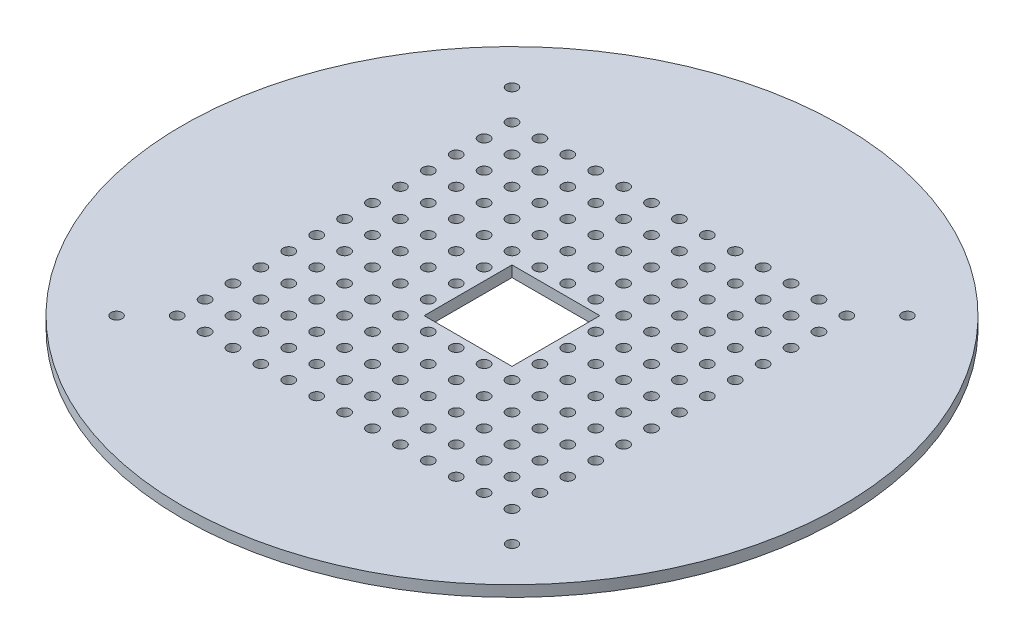
SolidWorks part; units mm, degrees
ref_plane "前视基准面" through (0, 0, 0) normal (0, 0, 1) x (1, 0, 0)
ref_plane "上视基准面" through (0, 0, 0) normal (0, 1, 0) x (1, 0, 0)
ref_plane "右视基准面" through (0, 0, 0) normal (1, 0, 0) x (0, 0, -1)
sketch "草图1" plane through (0, 0, 0) normal (0, 1, 0) x (1, 0, 0)
  line L0 (76.2, 76.2) -> (63.5, 76.2) construction
  circle A0 centre (0, 0) radius 150
  circle A1 centre (90, -90) radius 2.5
  circle A2 centre (90, 90) radius 2.5
  circle A3 centre (-90, -90) radius 2.5
  circle A4 centre (-90, 90) radius 2.5
  circle A5 centre (76.2, 76.2) radius 2.54
  circle A6 centre (63.5, 76.2) radius 2.54
  circle A7 centre (50.8, 76.2) radius 2.54
  circle A8 centre (38.1, 76.2) radius 2.54
  circle A9 centre (25.4, 76.2) radius 2.54
  circle A10 centre (12.7, 76.2) radius 2.54
  circle A11 centre (0, 76.2) radius 2.54
  circle A12 centre (-12.7, 76.2) radius 2.54
  circle A13 centre (-25.4, 76.2) radius 2.54
  circle A14 centre (-38.1, 76.2) radius 2.54
  circle A15 centre (-50.8, 76.2) radius 2.54
  circle A16 centre (-63.5, 76.2) radius 2.54
  circle A17 centre (-76.2, 76.2) radius 2.54
  circle A18 centre (63.5, 63.5) radius 2.54
  circle A19 centre (50.8, 63.5) radius 2.54
  circle A20 centre (38.1, 63.5) radius 2.54
  circle A21 centre (25.4, 63.5) radius 2.54
  circle A22 centre (12.7, 63.5) radius 2.54
  circle A23 centre (0, 63.5) radius 2.54
  circle A24 centre (-12.7, 63.5) radius 2.54
  circle A25 centre (-25.4, 63.5) radius 2.54
  circle A26 centre (-38.1, 63.5) radius 2.54
  circle A27 centre (-50.8, 63.5) radius 2.54
  circle A28 centre (-63.5, 63.5) radius 2.54
  circle A29 centre (-76.2, 63.5) radius 2.54
  circle A30 centre (63.5, 50.8) radius 2.54
  circle A31 centre (50.8, 50.8) radius 2.54
  circle A32 centre (38.1, 50.8) radius 2.54
  circle A33 centre (25.4, 50.8) radius 2.54
  circle A34 centre (12.7, 50.8) radius 2.54
  circle A35 centre (0, 50.8) radius 2.54
  circle A36 centre (-12.7, 50.8) radius 2.54
  circle A37 centre (-25.4, 50.8) radius 2.54
  circle A38 centre (-38.1, 50.8) radius 2.54
  circle A39 centre (-50.8, 50.8) radius 2.54
  circle A40 centre (-63.5, 50.8) radius 2.54
  circle A41 centre (-76.2, 50.8) radius 2.54
  circle A42 centre (63.5, 38.1) radius 2.54
  circle A43 centre (50.8, 38.1) radius 2.54
  circle A44 centre (38.1, 38.1) radius 2.54
  circle A45 centre (25.4, 38.1) radius 2.54
  circle A46 centre (12.7, 38.1) radius 2.54
  circle A47 centre (0, 38.1) radius 2.54
  circle A48 centre (-12.7, 38.1) radius 2.54
  circle A49 centre (-25.4, 38.1) radius 2.54
  circle A50 centre (-38.1, 38.1) radius 2.54
  circle A51 centre (-50.8, 38.1) radius 2.54
  circle A52 centre (-63.5, 38.1) radius 2.54
  circle A53 centre (-76.2, 38.1) radius 2.54
  circle A54 centre (63.5, 25.4) radius 2.54
  circle A55 centre (50.8, 25.4) radius 2.54
  circle A56 centre (38.1, 25.4) radius 2.54
  circle A57 centre (25.4, 25.4) radius 2.54
  circle A58 centre (12.7, 25.4) radius 2.54
  circle A59 centre (0, 25.4) radius 2.54
  circle A60 centre (-12.7, 25.4) radius 2.54
  circle A61 centre (-25.4, 25.4) radius 2.54
  circle A62 centre (-38.1, 25.4) radius 2.54
  circle A63 centre (-50.8, 25.4) radius 2.54
  circle A64 centre (-63.5, 25.4) radius 2.54
  circle A65 centre (-76.2, 25.4) radius 2.54
  circle A66 centre (63.5, 12.7) radius 2.54
  circle A67 centre (50.8, 12.7) radius 2.54
  circle A68 centre (38.1, 12.7) radius 2.54
  circle A69 centre (25.4, 12.7) radius 2.54
  circle A70 centre (12.7, 12.7) radius 2.54
  circle A71 centre (0, 12.7) radius 2.54
  circle A72 centre (-12.7, 12.7) radius 2.54
  circle A73 centre (-25.4, 12.7) radius 2.54
  circle A74 centre (-38.1, 12.7) radius 2.54
  circle A75 centre (-50.8, 12.7) radius 2.54
  circle A76 centre (-63.5, 12.7) radius 2.54
  circle A77 centre (-76.2, 12.7) radius 2.54
  circle A78 centre (63.5, 0) radius 2.54
  circle A79 centre (50.8, 0) radius 2.54
  circle A80 centre (38.1, 0) radius 2.54
  circle A81 centre (25.4, 0) radius 2.54
  circle A82 centre (12.7, 0) radius 2.54
  circle A83 centre (0, 0) radius 2.54
  circle A84 centre (-12.7, 0) radius 2.54
  circle A85 centre (-25.4, 0) radius 2.54
  circle A86 centre (-38.1, 0) radius 2.54
  circle A87 centre (-50.8, 0) radius 2.54
  circle A88 centre (-63.5, 0) radius 2.54
  circle A89 centre (-76.2, 0) radius 2.54
  circle A90 centre (63.5, -12.7) radius 2.54
  circle A91 centre (50.8, -12.7) radius 2.54
  circle A92 centre (38.1, -12.7) radius 2.54
  circle A93 centre (25.4, -12.7) radius 2.54
  circle A94 centre (12.7, -12.7) radius 2.54
  circle A95 centre (0, -12.7) radius 2.54
  circle A96 centre (-12.7, -12.7) radius 2.54
  circle A97 centre (-25.4, -12.7) radius 2.54
  circle A98 centre (-38.1, -12.7) radius 2.54
  circle A99 centre (-50.8, -12.7) radius 2.54
  circle A100 centre (-63.5, -12.7) radius 2.54
  circle A101 centre (-76.2, -12.7) radius 2.54
  circle A102 centre (63.5, -25.4) radius 2.54
  circle A103 centre (50.8, -25.4) radius 2.54
  circle A104 centre (38.1, -25.4) radius 2.54
  circle A105 centre (25.4, -25.4) radius 2.54
  circle A106 centre (12.7, -25.4) radius 2.54
  circle A107 centre (0, -25.4) radius 2.54
  circle A108 centre (-12.7, -25.4) radius 2.54
  circle A109 centre (-25.4, -25.4) radius 2.54
  circle A110 centre (-38.1, -25.4) radius 2.54
  circle A111 centre (-50.8, -25.4) radius 2.54
  circle A112 centre (-63.5, -25.4) radius 2.54
  circle A113 centre (-76.2, -25.4) radius 2.54
  circle A114 centre (63.5, -38.1) radius 2.54
  circle A115 centre (50.8, -38.1) radius 2.54
  circle A116 centre (38.1, -38.1) radius 2.54
  circle A117 centre (25.4, -38.1) radius 2.54
  circle A118 centre (12.7, -38.1) radius 2.54
  circle A119 centre (0, -38.1) radius 2.54
  circle A120 centre (-12.7, -38.1) radius 2.54
  circle A121 centre (-25.4, -38.1) radius 2.54
  circle A122 centre (-38.1, -38.1) radius 2.54
  circle A123 centre (-50.8, -38.1) radius 2.54
  circle A124 centre (-63.5, -38.1) radius 2.54
  circle A125 centre (-76.2, -38.1) radius 2.54
  circle A126 centre (63.5, -50.8) radius 2.54
  circle A127 centre (50.8, -50.8) radius 2.54
  circle A128 centre (38.1, -50.8) radius 2.54
  circle A129 centre (25.4, -50.8) radius 2.54
  circle A130 centre (12.7, -50.8) radius 2.54
  circle A131 centre (0, -50.8) radius 2.54
  circle A132 centre (-12.7, -50.8) radius 2.54
  circle A133 centre (-25.4, -50.8) radius 2.54
  circle A134 centre (-38.1, -50.8) radius 2.54
  circle A135 centre (-50.8, -50.8) radius 2.54
  circle A136 centre (-63.5, -50.8) radius 2.54
  circle A137 centre (-76.2, -50.8) radius 2.54
  circle A138 centre (63.5, -63.5) radius 2.54
  circle A139 centre (50.8, -63.5) radius 2.54
  circle A140 centre (38.1, -63.5) radius 2.54
  circle A141 centre (25.4, -63.5) radius 2.54
  circle A142 centre (12.7, -63.5) radius 2.54
  circle A143 centre (0, -63.5) radius 2.54
  circle A144 centre (-12.7, -63.5) radius 2.54
  circle A145 centre (-25.4, -63.5) radius 2.54
  circle A146 centre (-38.1, -63.5) radius 2.54
  circle A147 centre (-50.8, -63.5) radius 2.54
  circle A148 centre (-63.5, -63.5) radius 2.54
  circle A149 centre (-76.2, -63.5) radius 2.54
  circle A150 centre (63.5, -76.2) radius 2.54
  circle A151 centre (50.8, -76.2) radius 2.54
  circle A152 centre (38.1, -76.2) radius 2.54
  circle A153 centre (25.4, -76.2) radius 2.54
  circle A154 centre (12.7, -76.2) radius 2.54
  circle A155 centre (0, -76.2) radius 2.54
  circle A156 centre (-12.7, -76.2) radius 2.54
  circle A157 centre (-25.4, -76.2) radius 2.54
  circle A158 centre (-38.1, -76.2) radius 2.54
  circle A159 centre (-50.8, -76.2) radius 2.54
  circle A160 centre (-63.5, -76.2) radius 2.54
  circle A161 centre (-76.2, -76.2) radius 2.54
  circle A162 centre (76.2, 63.5) radius 2.54
  circle A163 centre (76.2, 50.8) radius 2.54
  circle A164 centre (76.2, 38.1) radius 2.54
  circle A165 centre (76.2, 25.4) radius 2.54
  circle A166 centre (76.2, 12.7) radius 2.54
  circle A167 centre (76.2, 0) radius 2.54
  circle A168 centre (76.2, -12.7) radius 2.54
  circle A169 centre (76.2, -25.4) radius 2.54
  circle A170 centre (76.2, -38.1) radius 2.54
  circle A171 centre (76.2, -50.8) radius 2.54
  circle A172 centre (76.2, -63.5) radius 2.54
  circle A173 centre (76.2, -76.2) radius 2.54
  dimension "D1" = 13
  dimension "D3" = 12.7
  dimension "D2" = 13
extrude "凸台-拉伸1" add sketch "草图1" along normal blind 5
sketch "草图2" plane through (0, 5, 0) normal (0, 1, 0) x (1, 0, 0)
  line L1 (-20, 20) -> (20, 20)
  line L2 (-20, 20) -> (-20, -20)
  line L3 (-20, -20) -> (20, -20)
  line L4 (20, 20) -> (20, -20)
  point P4 (0, 0)
  point P5 (0, 0)
  point P6 (0, 0)
extrude "切除-拉伸1" cut sketch "草图2" against normal through all
